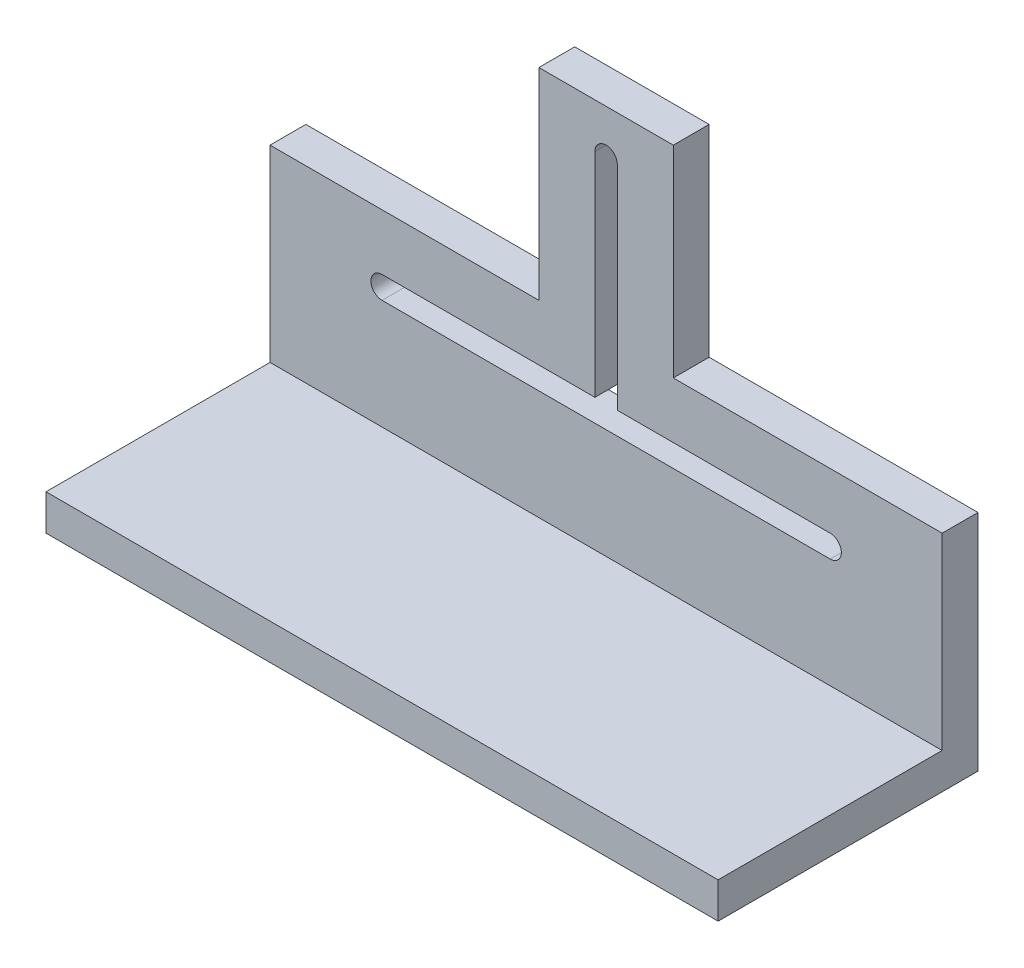
SolidWorks part; units mm, degrees
ref_plane "Front Plane" through (0, 0, 0) normal (0, 0, 1) x (1, 0, 0)
ref_plane "Top Plane" through (0, 0, 0) normal (0, 1, 0) x (1, 0, 0)
ref_plane "Right Plane" through (0, 0, 0) normal (1, 0, 0) x (0, 0, -1)
sketch "Sketch1" plane through (0, 0, 0) normal (0, 0, 1) x (1, 0, 0)
  line L0 (-2.5, 2.5) -> (-50, 2.5)
  line L1 (-2.5, 2.5) -> (-2.5, 50)
  line L2 (2.5, 50) -> (2.5, 2.5)
  line L3 (2.5, 2.5) -> (50, 2.5)
  line L4 (-50, -2.5) -> (50, -2.5)
  line L5 (0, 50) -> (0, 0) construction
  line L6 (0, 0) -> (50, 0) construction
  line L7 (-15, 15) -> (-15, 60)
  line L8 (-15, 60) -> (15, 60)
  line L9 (15, 60) -> (15, 15)
  line L10 (15, 15) -> (75, 15)
  line L11 (75, 15) -> (75, -35)
  line L12 (75, -35) -> (-75, -35)
  line L13 (-75, -35) -> (-75, 15)
  line L14 (-75, 15) -> (-15, 15)
  arc A0 (-50, 2.5) -> (-50, -2.5) centre (-50, 0) ccw
  arc A1 (-2.5, 50) -> (2.5, 50) centre (0, 50) cw
  arc A2 (50, 2.5) -> (50, -2.5) centre (50, 0) cw
  dimension "D2" = 2.5
  dimension "D1" = 100
  dimension "D3" = 50
  dimension "D4" = 30
  dimension "D5" = 15
  dimension "D6" = 45
  dimension "D7" = 50
  dimension "D8" = 150
extrude "Boss-Extrude1" add sketch "Sketch1" against normal blind 8
sketch "Sketch2" plane through (0, 0, 0) normal (0, 0, 1) x (1, 0, 0)
  line L0 (75, -35) -> (75, 15) construction
  line L1 (-75, -35) -> (75, -35)
  line L2 (-75, -35) -> (-75, -27)
  line L3 (-75, -27) -> (75, -27)
  line L4 (75, -35) -> (75, -27)
  dimension "D1" = 8
extrude "Boss-Extrude2" add sketch "Sketch2" along normal blind 50
